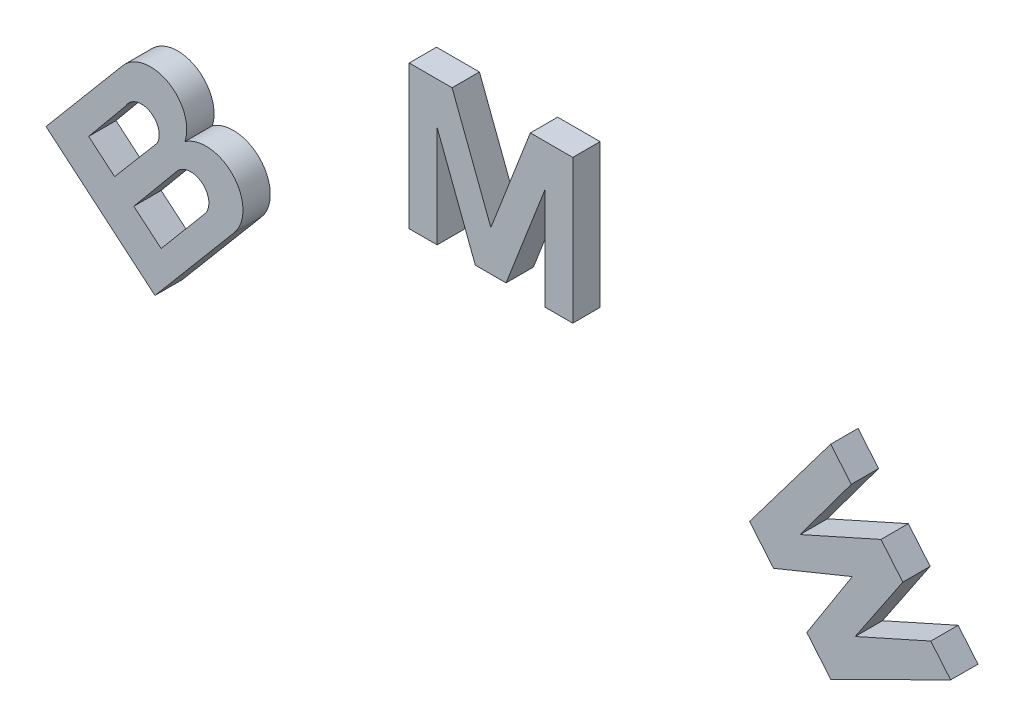
SolidWorks part; units mm, degrees
ref_plane "前视基准面" through (0, 0, 0) normal (0, 0, 1) x (1, 0, 0)
ref_plane "上视基准面" through (0, 0, 0) normal (0, 1, 0) x (1, 0, 0)
ref_plane "右视基准面" through (0, 0, 0) normal (1, 0, 0) x (0, 0, -1)
other "Configuration Table"
sketch "草图4" plane through (0, 0, 0) normal (0, 0, 1) x (1, 0, 0)
  line L0 (-32.5858, 21.0675) -> (-24.5818, 14.3186)
  line L1 (-24.5818, 14.3186) -> (-18.6672, 21.3331)
  line L2 (-32.5858, 21.0675) -> (-26.8673, 27.8598)
  line L3 (-29.4331, 22.0067) -> (-27.5368, 20.4017)
  line L4 (-27.5368, 20.4017) -> (-24.4154, 24.0896)
  line L5 (-29.4331, 22.0067) -> (-26.7287, 25.2829)
  line L7 (-22.928, 23.0862) -> (-26.1312, 19.23)
  line L8 (-26.1312, 19.23) -> (-24.1325, 17.5488)
  line L9 (-24.1325, 17.5488) -> (-20.8446, 21.4575)
  line L10 (-5.9969, 38.4089) -> (-5.9969, 27.8598)
  line L11 (-5.9969, 27.8598) -> (-3.9128, 27.8598)
  line L12 (-3.9128, 27.8598) -> (-3.9128, 35.2187)
  line L13 (-3.9128, 35.2187) -> (-1.1506, 27.9722)
  line L14 (-1.1506, 27.9722) -> (1.1264, 27.9722)
  line L15 (1.1264, 27.9722) -> (3.9398, 35.2187)
  line L16 (3.9398, 35.2187) -> (3.9398, 27.8598)
  line L17 (3.9398, 27.8598) -> (6.0143, 27.8598)
  line L18 (6.0143, 27.8598) -> (6.0143, 38.4089)
  line L19 (6.0143, 38.4089) -> (2.8764, 38.4089)
  line L20 (2.8764, 38.4089) -> (0, 31)
  line L21 (0, 31) -> (-2.8241, 38.4089)
  line L22 (-2.8241, 38.4089) -> (-5.9969, 38.4089)
  line L23 (24.8728, 29.6874) -> (26.4029, 27.8598)
  line L24 (26.4029, 27.8598) -> (22.6901, 22.8517)
  line L25 (22.6901, 22.8517) -> (28.5582, 25.4792)
  line L26 (28.5582, 25.4792) -> (30.1753, 23.5477)
  line L27 (30.1753, 23.5477) -> (26.7186, 18.4048)
  line L28 (26.7186, 18.4048) -> (32.2027, 20.8603)
  line L29 (32.2027, 20.8603) -> (33.6836, 19.0914)
  line L30 (33.6836, 19.0914) -> (24.8728, 14.7236)
  line L31 (24.8728, 14.7236) -> (23.0998, 16.8414)
  line L32 (23.0998, 16.8414) -> (26.4029, 22.0067)
  line L33 (26.4029, 22.0067) -> (20.6841, 19.668)
  line L34 (20.6841, 19.668) -> (18.9093, 21.7879)
  line L35 (18.9093, 21.7879) -> (24.8728, 29.6874)
  line L36 (-26.8673, 27.8598) -> (-26.5349, 28.1583)
  line L37 (-26.5349, 28.1583) -> (-26.1576, 28.3976)
  line L38 (-26.1576, 28.3976) -> (-25.746, 28.5711)
  line L39 (-25.746, 28.5711) -> (-25.3112, 28.6741)
  line L40 (-25.3112, 28.6741) -> (-24.8655, 28.7036)
  line L41 (-24.8655, 28.7036) -> (-24.421, 28.659)
  line L42 (-24.421, 28.659) -> (-23.99, 28.5414)
  line L43 (-23.99, 28.5414) -> (-23.5844, 28.3541)
  line L44 (-23.5844, 28.3541) -> (-23.2155, 28.1022)
  line L45 (-23.2155, 28.1022) -> (-22.8933, 27.7926)
  line L46 (-22.8933, 27.7926) -> (-22.6268, 27.4341)
  line L47 (-22.6268, 27.4341) -> (-22.4234, 27.0363)
  line L48 (-22.4234, 27.0363) -> (-22.2886, 26.6104)
  line L49 (-22.2886, 26.6104) -> (-22.2262, 26.168)
  line L50 (-22.2262, 26.168) -> (-22.2379, 25.7214)
  line L51 (-22.2379, 25.7214) -> (-22.3234, 25.2829)
  line L52 (-22.3234, 25.2829) -> (-21.9021, 25.5042)
  line L53 (-21.9021, 25.5042) -> (-21.4487, 25.649)
  line L54 (-21.4487, 25.649) -> (-20.9771, 25.713)
  line L55 (-20.9771, 25.713) -> (-20.5015, 25.6942)
  line L56 (-20.5015, 25.6942) -> (-20.0365, 25.5932)
  line L57 (-20.0365, 25.5932) -> (-19.5959, 25.4131)
  line L58 (-19.5959, 25.4131) -> (-19.1933, 25.1593)
  line L59 (-19.1933, 25.1593) -> (-18.8409, 24.8395)
  line L60 (-18.8409, 24.8395) -> (-18.5492, 24.4634)
  line L61 (-18.5492, 24.4634) -> (-18.3272, 24.0424)
  line L62 (-18.3272, 24.0424) -> (-18.1816, 23.5893)
  line L63 (-18.1816, 23.5893) -> (-18.1167, 23.1178)
  line L64 (-18.1167, 23.1178) -> (-18.1347, 22.6423)
  line L65 (-18.1347, 22.6423) -> (-18.2348, 22.177)
  line L66 (-18.2348, 22.177) -> (-18.4141, 21.7362)
  line L67 (-18.4141, 21.7362) -> (-18.6672, 21.3331)
  line L68 (-26.7287, 25.2829) -> (-26.6147, 25.4652)
  line L69 (-26.6147, 25.4652) -> (-26.4723, 25.6262)
  line L70 (-26.4723, 25.6262) -> (-26.3053, 25.7615)
  line L71 (-26.3053, 25.7615) -> (-26.1183, 25.8676)
  line L72 (-26.1183, 25.8676) -> (-25.9164, 25.9414)
  line L73 (-25.9164, 25.9414) -> (-25.7052, 25.9809)
  line L74 (-25.7052, 25.9809) -> (-25.4902, 25.9852)
  line L75 (-25.4902, 25.9852) -> (-25.2776, 25.954)
  line L76 (-25.2776, 25.954) -> (-25.0729, 25.8882)
  line L77 (-25.0729, 25.8882) -> (-24.8819, 25.7897)
  line L78 (-24.8819, 25.7897) -> (-24.7097, 25.661)
  line L79 (-24.7097, 25.661) -> (-24.561, 25.5058)
  line L80 (-24.561, 25.5058) -> (-24.4399, 25.3282)
  line L81 (-24.4399, 25.3282) -> (-24.3497, 25.1331)
  line L82 (-24.3497, 25.1331) -> (-24.2928, 24.9258)
  line L83 (-24.2928, 24.9258) -> (-24.2708, 24.712)
  line L84 (-24.2708, 24.712) -> (-24.2843, 24.4975)
  line L85 (-24.2843, 24.4975) -> (-24.3329, 24.2881)
  line L86 (-24.3329, 24.2881) -> (-24.4154, 24.0896)
  line L87 (-22.928, 23.0862) -> (-22.7556, 23.239)
  line L88 (-22.7556, 23.239) -> (-22.5595, 23.3597)
  line L89 (-22.5595, 23.3597) -> (-22.3455, 23.4447)
  line L90 (-22.3455, 23.4447) -> (-22.12, 23.4915)
  line L91 (-22.12, 23.4915) -> (-21.8898, 23.4986)
  line L92 (-21.8898, 23.4986) -> (-21.6619, 23.4658)
  line L93 (-21.6619, 23.4658) -> (-21.443, 23.3942)
  line L94 (-21.443, 23.3942) -> (-21.2398, 23.2858)
  line L95 (-21.2398, 23.2858) -> (-21.0583, 23.144)
  line L96 (-21.0583, 23.144) -> (-20.9041, 22.973)
  line L97 (-20.9041, 22.973) -> (-20.7818, 22.7778)
  line L98 (-20.7818, 22.7778) -> (-20.695, 22.5645)
  line L99 (-20.695, 22.5645) -> (-20.6463, 22.3394)
  line L100 (-20.6463, 22.3394) -> (-20.6373, 22.1093)
  line L101 (-20.6373, 22.1093) -> (-20.6681, 21.8811)
  line L102 (-20.6681, 21.8811) -> (-20.7379, 21.6616)
  line L103 (-20.7379, 21.6616) -> (-20.8446, 21.4575)
extrude "凸台-拉伸1" add sketch "草图4" along normal blind 2
sketch "草图5" plane through (0, 0, 2) normal (0, 0, 1) x (1, 0, 0)
  line L0 (-26.9445, 27.7371) -> (-32.5576, 21.0699)
  line L1 (-32.5576, 21.0699) -> (-24.5842, 14.3468)
  line L2 (-24.5842, 14.3468) -> (-18.7799, 21.2304)
  line L3 (-29.4611, 22.0042) -> (-27.5345, 20.3735)
  line L4 (-27.5345, 20.3735) -> (-24.5731, 23.8722)
  line L5 (-26.553, 25.5272) -> (-29.4611, 22.0042)
  line L6 (-5.9769, 27.8798) -> (-5.9769, 38.3889)
  line L7 (-26.7287, 25.2829) -> (-29.4331, 22.0067) construction
  line L8 (-27.5368, 20.4017) -> (-24.4154, 24.0896) construction
  line L9 (-29.4331, 22.0067) -> (-27.5368, 20.4017) construction
  line L10 (-26.8673, 27.8598) -> (-32.5858, 21.0675) construction
  line L11 (-32.5858, 21.0675) -> (-24.5818, 14.3186) construction
  line L12 (-24.5818, 14.3186) -> (-18.6672, 21.3331) construction
  line L13 (-22.9982, 23.0329) -> (-26.1592, 19.2275)
  line L14 (-26.1592, 19.2275) -> (-24.1301, 17.5206)
  line L15 (-24.1301, 17.5206) -> (-20.9404, 21.3126)
  line L16 (-22.928, 23.0862) -> (-26.1312, 19.23) construction
  line L17 (-26.1312, 19.23) -> (-24.1325, 17.5488) construction
  line L18 (-24.1325, 17.5488) -> (-20.8446, 21.4575) construction
  line L19 (-5.9769, 38.3889) -> (-2.8379, 38.3889)
  line L20 (-2.8379, 38.3889) -> (-0.0002, 30.9443)
  line L21 (-0.0002, 30.9443) -> (2.8901, 38.3889)
  line L22 (2.8901, 38.3889) -> (5.9943, 38.3889)
  line L23 (5.9943, 38.3889) -> (5.9943, 27.8798)
  line L24 (5.9943, 27.8798) -> (3.9598, 27.8798)
  line L25 (3.9598, 27.8798) -> (3.9598, 35.3255)
  line L26 (3.9598, 35.3255) -> (1.1127, 27.9922)
  line L27 (1.1127, 27.9922) -> (-1.1368, 27.9922)
  line L28 (-1.1368, 27.9922) -> (-3.9328, 35.3273)
  line L29 (-3.9328, 35.3273) -> (-3.9328, 27.8798)
  line L30 (-3.9328, 27.8798) -> (-5.9769, 27.8798)
  line L31 (-5.9969, 38.4089) -> (-5.9969, 27.8598) construction
  line L32 (-5.9969, 27.8598) -> (-3.9128, 27.8598) construction
  line L33 (-3.9128, 27.8598) -> (-3.9128, 35.2187) construction
  line L34 (-3.9128, 35.2187) -> (-1.1506, 27.9722) construction
  line L35 (-1.1506, 27.9722) -> (1.1264, 27.9722) construction
  line L36 (0, 31) -> (-2.8241, 38.4089) construction
  line L37 (-2.8241, 38.4089) -> (-5.9969, 38.4089) construction
  line L38 (2.8764, 38.4089) -> (0, 31) construction
  line L39 (1.1264, 27.9722) -> (3.9398, 35.2187) construction
  line L40 (3.9398, 35.2187) -> (3.9398, 27.8598) construction
  line L41 (3.9398, 27.8598) -> (6.0143, 27.8598) construction
  line L42 (6.0143, 27.8598) -> (6.0143, 38.4089) construction
  line L43 (6.0143, 38.4089) -> (2.8764, 38.4089) construction
  line L44 (24.8736, 29.6553) -> (18.9348, 21.7885)
  line L45 (18.9348, 21.7885) -> (20.69, 19.692)
  line L46 (20.69, 19.692) -> (26.4537, 22.0491)
  line L47 (26.4537, 22.0491) -> (23.1245, 16.843)
  line L48 (23.1245, 16.843) -> (24.8781, 14.7485)
  line L49 (24.8781, 14.7485) -> (33.652, 19.098)
  line L50 (33.652, 19.098) -> (32.1971, 20.8358)
  line L51 (32.1971, 20.8358) -> (26.663, 18.358)
  line L52 (26.663, 18.358) -> (30.1503, 23.5464)
  line L53 (30.1503, 23.5464) -> (28.5526, 25.4547)
  line L54 (28.5526, 25.4547) -> (22.6285, 22.8022)
  line L55 (22.6285, 22.8022) -> (26.3774, 27.8591)
  line L56 (26.3774, 27.8591) -> (24.8736, 29.6553)
  line L57 (18.9093, 21.7879) -> (20.6841, 19.668) construction
  line L58 (24.8728, 29.6874) -> (18.9093, 21.7879) construction
  line L59 (22.6901, 22.8517) -> (26.4029, 27.8598) construction
  line L60 (26.4029, 27.8598) -> (24.8728, 29.6874) construction
  line L61 (28.5582, 25.4792) -> (22.6901, 22.8517) construction
  line L62 (20.6841, 19.668) -> (26.4029, 22.0067) construction
  line L63 (30.1753, 23.5477) -> (28.5582, 25.4792) construction
  line L64 (26.7186, 18.4048) -> (30.1753, 23.5477) construction
  line L65 (26.4029, 22.0067) -> (23.0998, 16.8414) construction
  line L66 (23.0998, 16.8414) -> (24.8728, 14.7236) construction
  line L67 (32.2027, 20.8603) -> (26.7186, 18.4048) construction
  line L68 (33.6836, 19.0914) -> (32.2027, 20.8603) construction
  line L69 (24.8728, 14.7236) -> (33.6836, 19.0914) construction
  circle A0 centre (-25.558, 24.7058) radius 1.2903
  circle A1 centre (-21.9666, 22.1759) radius 1.3411
  circle A2 centre (-24.9122, 26.0262) radius 2.6566
  circle A3 centre (-20.8497, 22.9756) radius 2.7074
  dimension "D1" = 0.02
  dimension "D2" = 0.02
  dimension "D3" = 0.02
  dimension "D4" = 4.5837
  dimension "D5" = 0.02
  dimension "D6" = 0.02
  dimension "D7" = 0.02
  dimension "D8" = 0.02
  dimension "D9" = 0.02
  dimension "D10" = 0.02
  dimension "D11" = 4.947
  dimension "D12" = 0.02
  dimension "D13" = 0.02
  dimension "D14" = 0.02
  dimension "D15" = 0.02
  dimension "D16" = 0.02
  dimension "D17" = 0.02
  dimension "D18" = 0.02
  dimension "D19" = 0.02
  dimension "D20" = 0.02
  dimension "D21" = 0.02
  dimension "D22" = 0.02
  dimension "D23" = 0.02
  dimension "D24" = 0.02
  dimension "D25" = 0.02
  dimension "D26" = 0.02
  dimension "D27" = 0.02
  dimension "D28" = 0.02
  dimension "D29" = 0.02
  dimension "D30" = 0.02
  dimension "D31" = 0.02
  dimension "D32" = 0.02
  dimension "D33" = 0.02
  dimension "D34" = 0.02
  dimension "D35" = 0.02
  dimension "D36" = 0.02
  dimension "D37" = 0.02
sketch "草图6" plane through (0, 0, 0) normal (0, 0, 1) x (1, 0, 0)
  line L0 (-26.9445, 27.7371) -> (-32.5576, 21.0699)
  line L1 (-32.5576, 21.0699) -> (-24.5842, 14.3468)
  line L2 (-24.5842, 14.3468) -> (-18.7799, 21.2304)
  line L3 (-29.4611, 22.0042) -> (-27.5345, 20.3735)
  line L4 (-27.5345, 20.3735) -> (-24.5731, 23.8722)
  line L5 (-26.553, 25.5272) -> (-29.4611, 22.0042)
  line L6 (-5.9769, 27.8798) -> (-5.9769, 38.3889)
  line L13 (-22.9982, 23.0329) -> (-26.1592, 19.2275)
  line L14 (-26.1592, 19.2275) -> (-24.1301, 17.5206)
  line L15 (-24.1301, 17.5206) -> (-20.9404, 21.3126)
  line L19 (-5.9769, 38.3889) -> (-2.8379, 38.3889)
  line L20 (-2.8379, 38.3889) -> (-0.0002, 30.9443)
  line L21 (-0.0002, 30.9443) -> (2.8901, 38.3889)
  line L22 (2.8901, 38.3889) -> (5.9943, 38.3889)
  line L23 (5.9943, 38.3889) -> (5.9943, 27.8798)
  line L24 (5.9943, 27.8798) -> (3.9598, 27.8798)
  line L25 (3.9598, 27.8798) -> (3.9598, 35.3255)
  line L26 (3.9598, 35.3255) -> (1.1127, 27.9922)
  line L27 (1.1127, 27.9922) -> (-1.1368, 27.9922)
  line L28 (-1.1368, 27.9922) -> (-3.9328, 35.3273)
  line L29 (-3.9328, 35.3273) -> (-3.9328, 27.8798)
  line L30 (-3.9328, 27.8798) -> (-5.9769, 27.8798)
  line L44 (24.8736, 29.6553) -> (18.9348, 21.7885)
  line L45 (18.9348, 21.7885) -> (20.69, 19.692)
  line L46 (20.69, 19.692) -> (26.4537, 22.0491)
  line L47 (26.4537, 22.0491) -> (23.1245, 16.843)
  line L48 (23.1245, 16.843) -> (24.8781, 14.7485)
  line L49 (24.8781, 14.7485) -> (33.652, 19.098)
  line L50 (33.652, 19.098) -> (32.1971, 20.8358)
  line L51 (32.1971, 20.8358) -> (26.663, 18.358)
  line L52 (26.663, 18.358) -> (30.1503, 23.5464)
  line L53 (30.1503, 23.5464) -> (28.5526, 25.4547)
  line L54 (28.5526, 25.4547) -> (22.6285, 22.8022)
  line L55 (22.6285, 22.8022) -> (26.3774, 27.8591)
  line L56 (26.3774, 27.8591) -> (24.8736, 29.6553)
  line L71 (-47.5366, 49.4553) -> (39.3499, 49.4553)
  line L72 (-47.5366, 49.4553) -> (-47.5366, 4.1032)
  line L73 (-47.5366, 4.1032) -> (39.3499, 4.1032)
  line L74 (39.3499, 49.4553) -> (39.3499, 4.1032)
  arc A0 (-24.5731, 23.8722) -> (-26.553, 25.5272) centre (-25.558, 24.7058) ccw
  arc A2 (-22.3856, 25.2052) -> (-26.9445, 27.7371) centre (-24.9122, 26.0262) ccw
  arc A4 (-20.9404, 21.3126) -> (-22.9982, 23.0329) centre (-21.9666, 22.1759) ccw
  arc A5 (-18.7799, 21.2304) -> (-22.3856, 25.2052) centre (-20.8497, 22.9756) ccw
  dimension "D4" = 4.5837
  dimension "D11" = 4.947
extrude "切除-拉伸1" cut sketch "草图6" along normal through all contours L74 L71 L72 L73 A5 L2 L1 L0 A2 L56 L55 L54 L53 L52 L51 L50 L49 L48 L47 L46 L45 L44 L29 L30 L6 L19 L20 L21 L22 L23 L24 L25 L26 L27 L28
